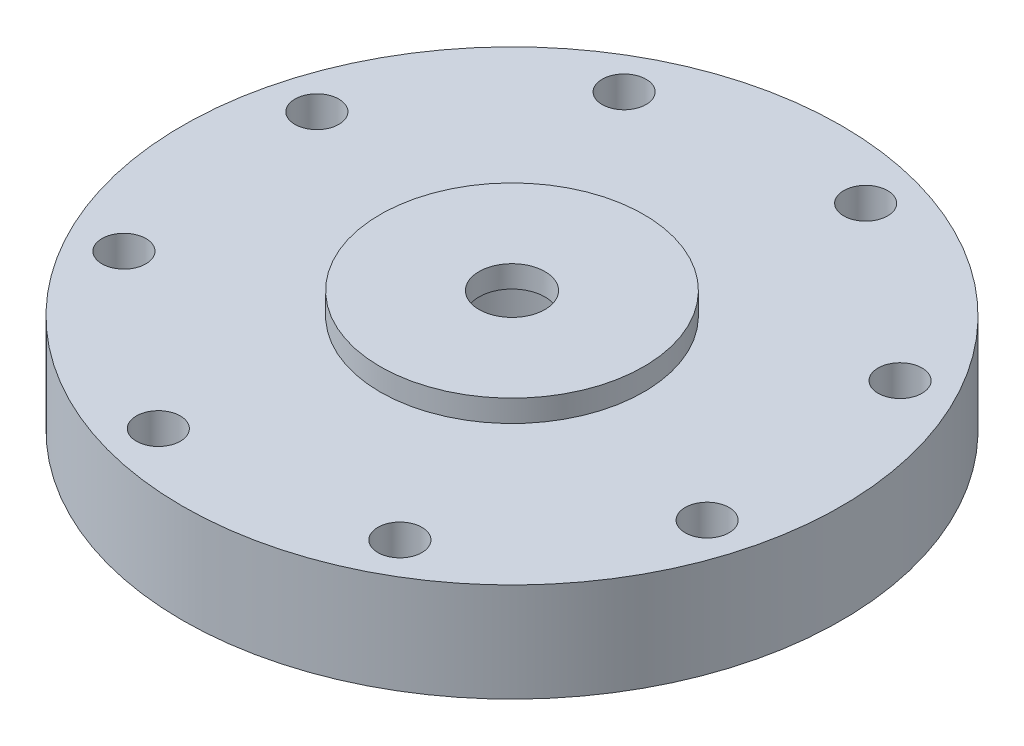
SolidWorks part; units mm, degrees
ref_plane "正面" through (0, 0, 0) normal (0, 0, 1) x (1, 0, 0)
ref_plane "平面" through (0, 0, 0) normal (0, 1, 0) x (1, 0, 0)
ref_plane "右側面" through (0, 0, 0) normal (1, 0, 0) x (0, 0, -1)
sketch "ｽｹｯﾁ1" plane through (0, 0, 0) normal (0, 1, 0) x (1, 0, 0)
  circle A0 centre (0, 0) radius 15
  dimension "D1" = 30
extrude "ﾎﾞｽ - 押し出し1" add sketch "ｽｹｯﾁ1" along normal mid plane 4.5
sketch "ｽｹｯﾁ2" plane through (0, 2.25, 0) normal (0, 1, 0) x (1, 0, 0)
  circle A0 centre (0, 0) radius 6
  dimension "D1" = 12
extrude "ﾎﾞｽ - 押し出し2" add sketch "ｽｹｯﾁ2" along normal blind 1
sketch "ｽｹｯﾁ3" plane through (0, 2.25, 0) normal (0, 1, 0) x (1, 0, 0)
  circle A0 centre (-11.3826, -6.2799) radius 1
  circle A1 centre (0, 0) radius 15 construction
  circle A2 centre (-12.4893, 3.6081) radius 1
  circle A3 centre (-6.2799, 11.3826) radius 1
  circle A4 centre (3.6081, 12.4893) radius 1
  circle A5 centre (11.3826, 6.2799) radius 1
  circle A6 centre (12.4893, -3.6081) radius 1
  circle A7 centre (6.2799, -11.3826) radius 1
  circle A8 centre (-3.6081, -12.4893) radius 1
  dimension "D1" = 2
  dimension "D2" = 13
  dimension "D3" = 8
extrude "ｶｯﾄ - 押し出し1" cut sketch "ｽｹｯﾁ3" against normal blind 5
sketch "ｽｹｯﾁ4" plane through (0, -2.25, 0) normal (0, -1, 0) x (1, 0, 0)
  circle A0 centre (0, 0) radius 4
  dimension "D1" = 8
extrude "ｶｯﾄ - 押し出し2" cut sketch "ｽｹｯﾁ4" against normal blind 4.5
sketch "ｽｹｯﾁ5" plane through (0, 3.25, 0) normal (0, 1, 0) x (1, 0, 0)
  circle A0 centre (0, 0) radius 1.5
  dimension "D1" = 3
extrude "ｶｯﾄ - 押し出し3" cut sketch "ｽｹｯﾁ5" against normal blind 4.5
